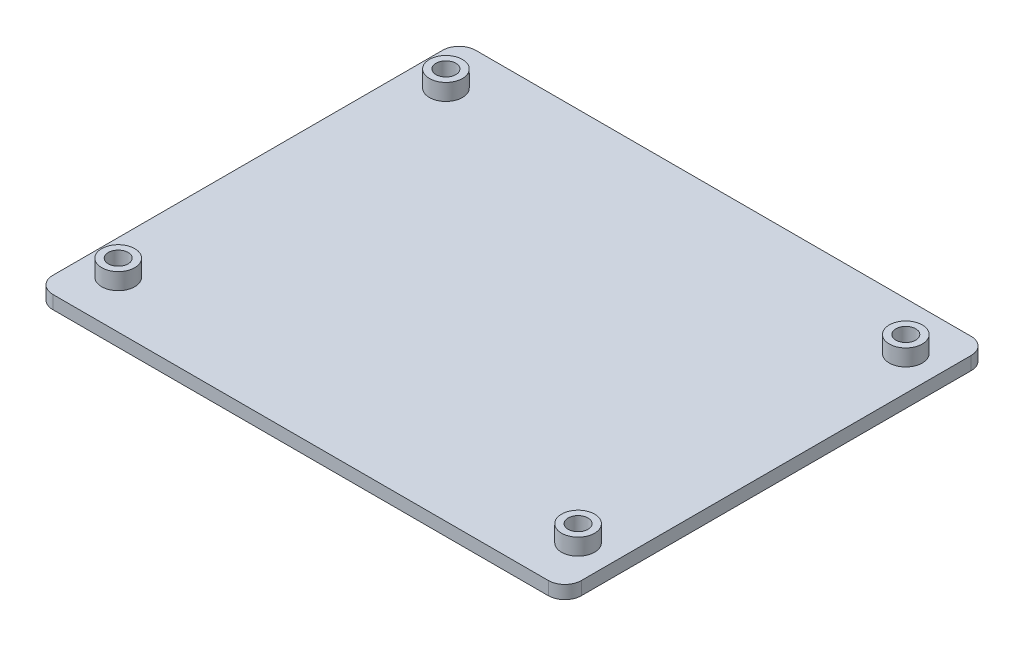
SolidWorks part; units mm, degrees
ref_plane "Front Plane" through (0, 0, 0) normal (0, 0, 1) x (1, 0, 0)
ref_plane "Top Plane" through (0, 0, 0) normal (0, 1, 0) x (1, 0, 0)
ref_plane "Right Plane" through (0, 0, 0) normal (1, 0, 0) x (0, 0, -1)
sketch "Sketch1" plane through (0, 0, 0) normal (0, 1, 0) x (1, 0, 0)
  line L1 (-40, -32) -> (40, -32)
  line L2 (-40, -32) -> (-40, 32)
  line L3 (-40, 32) -> (40, 32)
  line L4 (40, -32) -> (40, 32)
  line L5 (-40, -32) -> (40, 32) construction
  line L6 (-40, 32) -> (40, -32) construction
  point P0 (0, 0)
  dimension "D1" = 80
  dimension "D2" = 64
extrude "Boss-Extrude1" add sketch "Sketch1" along normal blind 2
fillet "Fillet1" radius 2.5 4 edges at (-40, 1, -32) (40, 1, -32) (-40, 1, 32) (40, 1, 32)
extrude "Cut-Extrude1" cut sketch "Sketch2" against normal up to surface (2 mm away) up to face at (0, 0, 0)
sketch "Sketch2" plane through (-9.0189, 2, 9.4633) normal (0, 1, 0) x (1, 0, 0)
  circle A0 centre (-25.7811, 34.2633) radius 1.5
  circle A1 centre (43.8189, 34.2633) radius 1.5
  circle A2 centre (43.8189, -15.3367) radius 1.5
  circle A3 centre (-25.7811, -15.3367) radius 1.5
sketch "Sketch3" plane through (0, 2, 0) normal (0, 1, 0) x (1, 0, 0)
  circle A0 centre (-34.8, 24.8) radius 2.5
  circle A1 centre (34.8, 24.8) radius 2.5
  circle A2 centre (34.8, -24.8) radius 2.5
  circle A3 centre (-34.8, -24.8) radius 2.5
  circle M1 centre (-34.8, -24.8) radius 1.5
  circle M2 centre (34.8, -24.8) radius 1.5
  circle M3 centre (34.8, 24.8) radius 1.5
  circle M4 centre (-34.8, 24.8) radius 1.5
extrude "Boss-Extrude2" add sketch "Sketch3" along normal blind 2.5 contours A0 M4 | A3 M1 | A1 M3 | A2 M2
